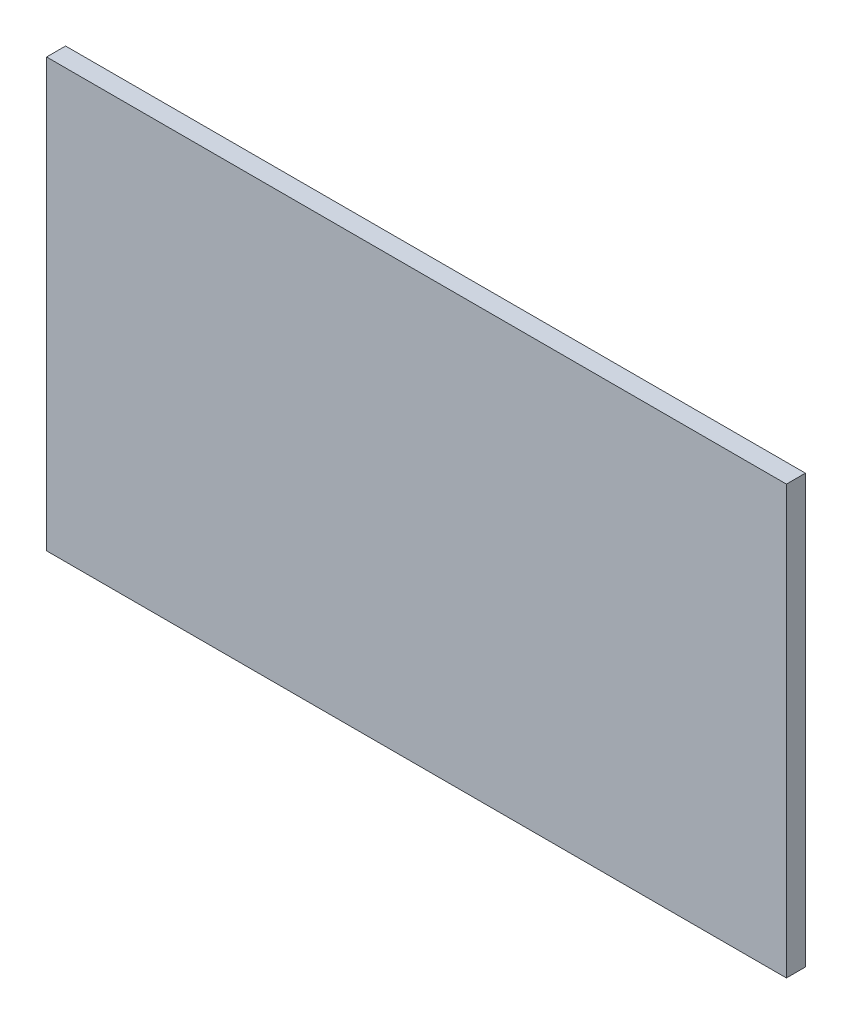
SolidWorks part; units mm, degrees
ref_plane "Front Plane" through (0, 0, 0) normal (0, 0, 1) x (1, 0, 0)
ref_plane "Top Plane" through (0, 0, 0) normal (0, 1, 0) x (1, 0, 0)
ref_plane "Right Plane" through (0, 0, 0) normal (1, 0, 0) x (0, 0, -1)
sketch "Sketch1" plane through (0, 0, 0) normal (0, 0, 1) x (1, 0, 0)
  line L1 (-148.49, -85.85) -> (148.49, -85.85)
  line L2 (-148.49, -85.85) -> (-148.49, 85.85)
  line L3 (-148.49, 85.85) -> (148.49, 85.85)
  line L4 (148.49, -85.85) -> (148.49, 85.85)
  line L5 (-148.49, -85.85) -> (148.49, 85.85) construction
  line L6 (-148.49, 85.85) -> (148.49, -85.85) construction
  point P0 (0, 0)
  dimension "D1" = 171.7
  dimension "D2" = 296.98
extrude "Boss-Extrude1" add sketch "Sketch1" along normal blind 7.62
